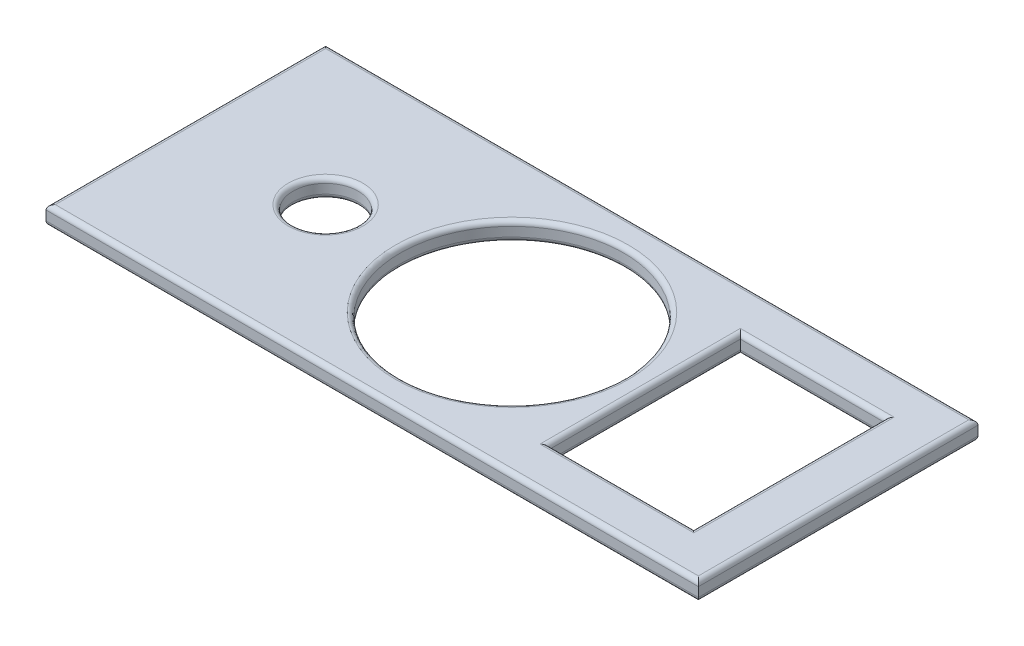
SolidWorks part; units mm, degrees
ref_plane "Front Plane" through (0, 0, 0) normal (0, 0, 1) x (1, 0, 0)
ref_plane "Top Plane" through (0, 0, 0) normal (0, 1, 0) x (1, 0, 0)
ref_plane "Right Plane" through (0, 0, 0) normal (1, 0, 0) x (0, 0, -1)
sketch "Sketch1" plane through (0, 0, 0) normal (0, 1, 0) x (1, 0, 0)
  line L1 (35, -15) -> (-35, -15)
  line L2 (35, -15) -> (35, 15)
  line L3 (35, 15) -> (-35, 15)
  line L4 (-35, -15) -> (-35, 15)
  line L5 (0, 15) -> (0, -15) construction
  line L6 (35, 0) -> (-35, 0) construction
  line L7 (29.75, -10.25) -> (14.25, -10.25)
  line L8 (29.75, -10.25) -> (29.75, 10.25)
  line L9 (29.75, 10.25) -> (14.25, 10.25)
  line L10 (14.25, -10.25) -> (14.25, 10.25)
  line L11 (22, 10.25) -> (22, -10.25) construction
  line L12 (29.75, 0) -> (14.25, 0) construction
  circle A0 centre (0, 0) radius 12
  circle A1 centre (-20, 0) radius 3.5
  point P0 (0, 0)
  point P8 (22, 0)
  dimension "D1" = 24
  dimension "D2" = 7
  dimension "D3" = 20.5
  dimension "D4" = 15.5
  dimension "D5" = 15
  dimension "D6" = 22
  dimension "D7" = 30
  dimension "D8" = 70
extrude "Boss-Extrude1" add sketch "Sketch1" along normal blind 2
fillet "Fillet1" radius 0.5 20 edges at (22, 0, -10.25) (29.75, 0, 0) (22, 0, 10.25) (14.25, 0, 0) (0, 0, 15) (35, 0, 0) (0, 0, -15) (-35, 0, 0) (0, 0, 12) (-20, 0, 3.5) (29.75, 2, 0) (22, 2, -10.25) (14.25, 2, 0) (22, 2, 10.25) (-20, 2, 3.5) (0, 2, -15) (35, 2, 0) (0, 2, 15) (-35, 2, 0) (0, 2, 12)
